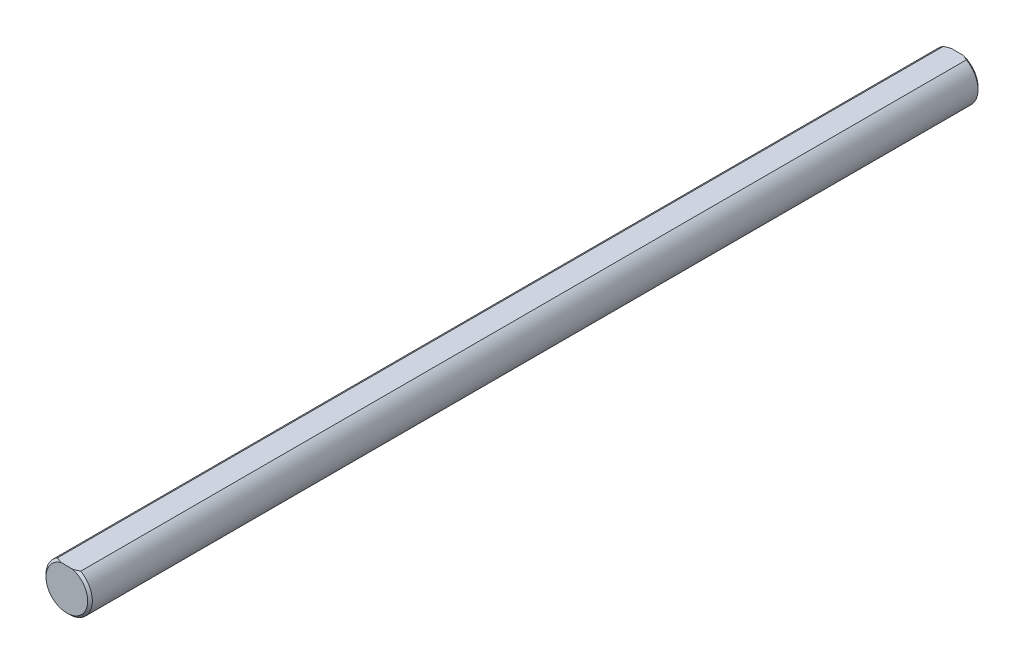
SolidWorks part; units mm, degrees
ref_plane "Front Plane" through (0, 0, 0) normal (0, 0, 1) x (1, 0, 0)
ref_plane "Top Plane" through (0, 0, 0) normal (0, 1, 0) x (1, 0, 0)
ref_plane "Right Plane" through (0, 0, 0) normal (1, 0, 0) x (0, 0, -1)
sketch "Sketch1" plane through (0, 0, 0) normal (0, 0, 1) x (1, 0, 0)
  circle A1 centre (0, 0) radius 7.9375 construction
  dimension "Diameter" = 15.875
sketch "Sketch2" plane through (0, 0, 0) normal (1, 0, 0) x (0, 0, -1)
  line L0 (-152.4, 7.9375) -> (152.4, 7.9375) construction
  line L1 (0, 7.9375) -> (0, -7.9375) construction
  line L2 (0, 7.9375) -> (0, -7.9375) construction
  point P2 (0, 7.9375)
  point P3 (120.65, 7.9375)
  point P4 (-120.65, 7.9375)
  dimension "Length" = 304.8
  dimension "D2" = 31.75
  dimension "D1" = 31.75
sketch "Sketch3" plane through (0, 0, 0) normal (0, 0, 1) x (1, 0, 0)
  circle A1 centre (0, 0) radius 7.9375 construction
  circle A3 centre (0, 0) radius 7.9375
extrude "Boss-Extrude2" add sketch "Sketch3" along normal up to vertex (152.4 mm away) and the other way up to vertex (152.4 mm away) up to point (0, 7.9375, 152.4) other way up to point (0, 7.9375, -152.4)
sketch "Sketch10" plane through (0, 0, 0) normal (0, 0, 1) x (1, 0, 0)
  line L0 (-3.9688, 6.8741) -> (3.9688, 6.8741)
  line L1 (0, 0) -> (0, 7.9375) construction
  circle A0 centre (0, 0) radius 7.9375 construction
  circle A1 centre (0, 0) radius 7.9375 construction
  arc A2 (-3.9688, 6.8741) -> (3.9688, 6.8741) centre (0, 0) cw
extrude "Cut-Extrude5" cut sketch "Sketch10" against normal through all both and the other way through all
chamfer "Chamfer1" distance 0.7937 angle 45 4 edges at (0, -7.9375, 152.4) (0, -7.9375, -152.4) (0, 6.8741, -152.4) (0, 6.8741, 152.4)
equation "\"D1@Chamfer1\"= \"Diameter@Sketch1\" / 20"
equation "\"D1@Sketch2\"=\"Diameter@Sketch1\"*2"
equation "\"D2@Sketch2\"=\"D1@Sketch2\""
